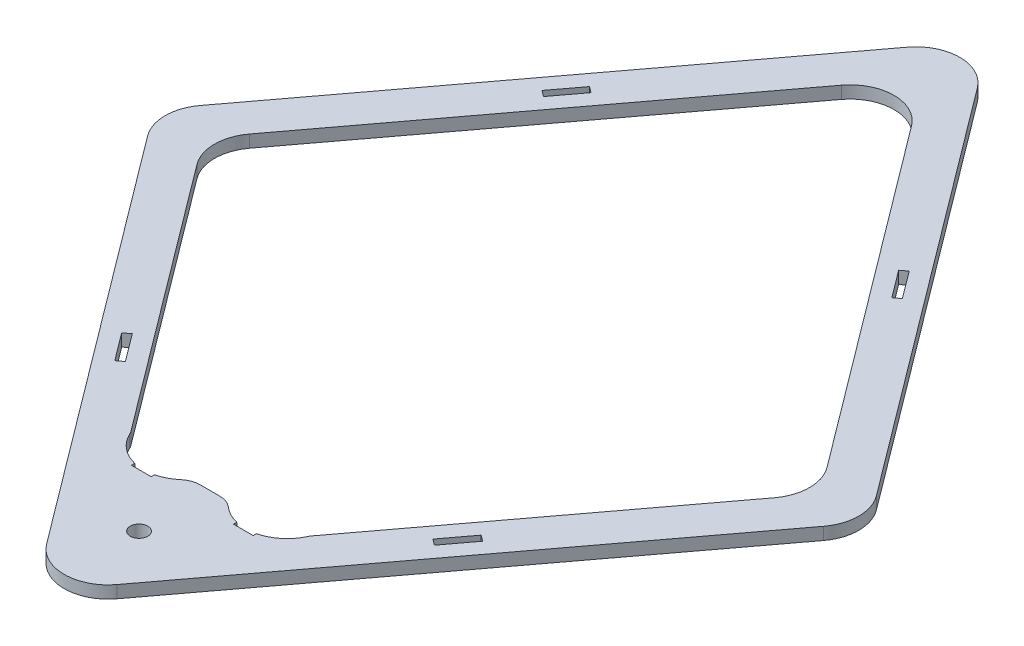
SolidWorks part; units mm, degrees
ref_plane "Front Plane" through (0, 0, 0) normal (0, 0, 1) x (1, 0, 0)
ref_plane "Top Plane" through (0, 0, 0) normal (0, 1, 0) x (1, 0, 0)
ref_plane "Right Plane" through (0, 0, 0) normal (1, 0, 0) x (0, 0, -1)
sketch "Sketch1" plane through (0, 0, 0) normal (0, 1, 0) x (1, 0, 0)
  line L4 (-214.4134, 14.4826) -> (-114.5848, -118.6222)
  line L6 (-33.0545, -118.6222) -> (66.7741, 14.4826)
  line L7 (-214.4134, 14.4826) -> (-73.8197, 201.941)
  line L9 (-82.3387, -123.2588) -> (-65.3006, -123.2588)
  line L10 (-73.8197, 201.941) -> (66.7741, 14.4826)
  line L11 (-73.8197, -202.9757) -> (89.2741, 14.4826)
  line L15 (-236.9134, 14.4826) -> (-73.8197, -202.9757)
  line L17 (-236.9134, 14.4826) -> (-73.8197, 231.941)
  line L22 (-156.0897, -81.1574) -> (-153.3297, -79.0874)
  line L23 (-156.0897, -81.1574) -> (-146.6697, -93.7174)
  line L24 (-146.6697, -93.7174) -> (-143.9097, -91.6474)
  line L25 (-153.3297, -79.0874) -> (-143.9097, -91.6474)
  line L26 (8.4503, -81.1574) -> (5.6903, -79.0874)
  line L27 (8.4503, -81.1574) -> (-0.9697, -93.7174)
  line L28 (-0.9697, -93.7174) -> (-3.7297, -91.6474)
  line L29 (5.6903, -79.0874) -> (-3.7297, -91.6474)
  line L31 (-101.5697, -129.7182) -> (-101.5697, -131.2182)
  line L32 (-101.5697, -131.2182) -> (-92.5697, -131.2182)
  line L33 (-92.5697, -129.7182) -> (-92.5697, -131.2182)
  line L35 (-55.0697, -129.7182) -> (-55.0697, -131.2182)
  line L36 (-55.0697, -131.2182) -> (-46.0697, -131.2182)
  line L37 (-46.0697, -129.7182) -> (-46.0697, -131.2182)
  line L38 (-73.8197, 231.941) -> (89.2741, 14.4826)
  line L39 (-146.6697, 122.6826) -> (-155.9697, 110.2826)
  line L40 (-155.9697, 110.2826) -> (-153.2097, 108.2126)
  line L41 (-153.2097, 108.2126) -> (-143.9097, 120.6126)
  line L42 (-143.9097, 120.6126) -> (-146.6697, 122.6826)
  line L43 (-73.8197, 214.4826) -> (-223.8197, 14.4826) construction
  line L44 (-223.8197, 14.4826) -> (-73.8197, -185.5174) construction
  line L45 (-73.8197, -185.5174) -> (76.1803, 14.4826) construction
  line L46 (76.1803, 14.4826) -> (-73.8197, 214.4826) construction
  line L47 (-0.9697, 122.6826) -> (8.3303, 110.2826)
  line L48 (8.3303, 110.2826) -> (5.5703, 108.2126)
  line L49 (5.5703, 108.2126) -> (-3.7297, 120.6126)
  line L50 (-3.7297, 120.6126) -> (-0.9697, 122.6826)
  arc A1 (-114.5848, -118.6222) -> (-101.5697, -129.7182) centre (-97.0697, -111.2588) ccw
  arc A2 (-65.3006, -123.2588) -> (-55.0697, -129.7182) centre (-50.5697, -111.2588) ccw
  circle A4 centre (-73.8197, -155.5174) radius 4
  arc A5 (-92.5697, -129.7182) -> (-82.3387, -123.2588) centre (-97.0697, -111.2588) ccw
  arc A6 (-46.0697, -129.7182) -> (-33.0545, -118.6222) centre (-50.5697, -111.2588) ccw
  point P7 (-73.8197, -123.2588)
  point P12 (0, 0)
  point P25 (0, 0)
  point P28 (0, 0)
  point P37 (0, 0)
  point P39 (0, 0)
  point P40 (0, 0)
  point P41 (0, 0)
  point P42 (-154.5897, 109.2476)
  point P46 (-151.5926, 109.9258)
  point P51 (-153.9154, 109.9839)
  point P53 (-153.8283, 109.7516)
  point P55 (-155.1349, 110.129)
  point P56 (-154.6184, 109.4823)
  point P57 (-2.3497, -92.6824)
  point P58 (-154.7097, -80.1224)
  point P59 (6.9503, 109.2476)
  dimension "D2" = 38
  dimension "D3" = 38
  dimension "D8" = 8
  dimension "D4" = 46.5
  dimension "D5" = 12
  dimension "D11" = 3.45
  dimension "D12" = 15.7
  dimension "D13" = 3.45
  dimension "D14" = 15.7
  dimension "D20" = 1.5
  dimension "D21" = 9
  dimension "D22" = 9
  dimension "D23" = 1.5
  dimension "D24" = 4.5
  dimension "D25" = 4.5
  dimension "D6" = 18
  dimension "D15" = 18
  dimension "D18" = 3.45
  dimension "D19" = 15.5
  dimension "D27" = 400
  dimension "D28" = 300
  dimension "D16" = 117.15
  dimension "D17" = 250
  dimension "D29" = 117.15
  dimension "D30" = 117.15
  dimension "D32" = 15.5
  dimension "D33" = 3.45
  dimension "D35" = 117.15
  dimension "D36" = 30
  dimension "D7" = 9
  dimension "D10" = 9
  dimension "D26" = 9
  dimension "D31" = 9
  dimension "D9" = 0.25
extrude "Boss-Extrude1" add sketch "Sketch1" along normal blind 5.63
fillet "Fillet1" radius 20 4 edges at (-73.8197, 2.815, -231.941) (89.2741, 2.815, -14.4826) (-73.8197, 2.815, 202.9757) (-236.9134, 2.815, -14.4826)
fillet "Fillet2" radius 20 3 edges at (-214.4134, 2.815, -14.4826) (-73.8197, 2.815, -201.941) (66.7741, 2.815, -14.4826)
fillet "Fillet3" radius 10 4 edges at (-114.5848, 2.815, 118.6222) (-82.3387, 2.815, 123.2588) (-65.3006, 2.815, 123.2588) (-33.0545, 2.815, 118.6222)
equation "\"InnerSide\"= 162"
equation "\"Thick\"= 18"
equation "\"PropGuardRadius\"= 19"
equation "\"PropGuardDistance\"= 46.5"
equation "\"D2@Sketch1\"=\"PropGuardRadius\"*2"
equation "\"D3@Sketch1\"=\"PropGuardRadius\"*2"
equation "\"D4@Sketch1\"=\"PropGuardDistance\""
equation "\"ThickerAcrylic\"= 5.63"
equation "\"Attach length\"= 15.5"
equation "\"magnet diameter\"= 9"
equation "\"magnet depth\"= 1.5"
equation "\"D20@Sketch1\"=\"magnet depth\""
equation "\"D21@Sketch1\"=\"magnet diameter\""
equation "\"D22@Sketch1\"=\"magnet diameter\""
equation "\"D23@Sketch1\"=\"magnet depth\""
equation "\"D24@Sketch1\"=\"magnet diameter\"/2"
equation "\"D25@Sketch1\"=\"magnet diameter\"/2"
equation "\"D6@Sketch1\"=\"Thick\""
equation "\"D15@Sketch1\"=\"Thick\""
equation "\"D19@Sketch1\"=\"Attach length\""
equation "\"length\"=400"
equation "\"D27@Sketch1\"=\"length\""
equation "\"width\"=300"
equation "\"D28@Sketch1\"=\"width\""
equation "\"D32@Sketch1\"=\"Attach length\""
equation "\"D7@Sketch1\"=\"Thick\"/2"
equation "\"D10@Sketch1\"=\"Thick\"/2"
equation "\"D26@Sketch1\"=\"Thick\"/2"
equation "\"D31@Sketch1\"=\"Thick\"/2"
equation "\"fit\"= 0.5"
equation "\"thinner acrylic\"= 2.95"
equation "\"D9@Sketch1\"=\"fit\"/2"
equation "\"Attach width\"= \"thinner acrylic\" + \"fit\""
equation "\"D18@Sketch1\"=\"Attach width\""
equation "\"D13@Sketch1\"=\"Attach width\""
equation "\"D11@Sketch1\"=\"Attach width\""
equation "\"D33@Sketch1\"=\"Attach width\""
